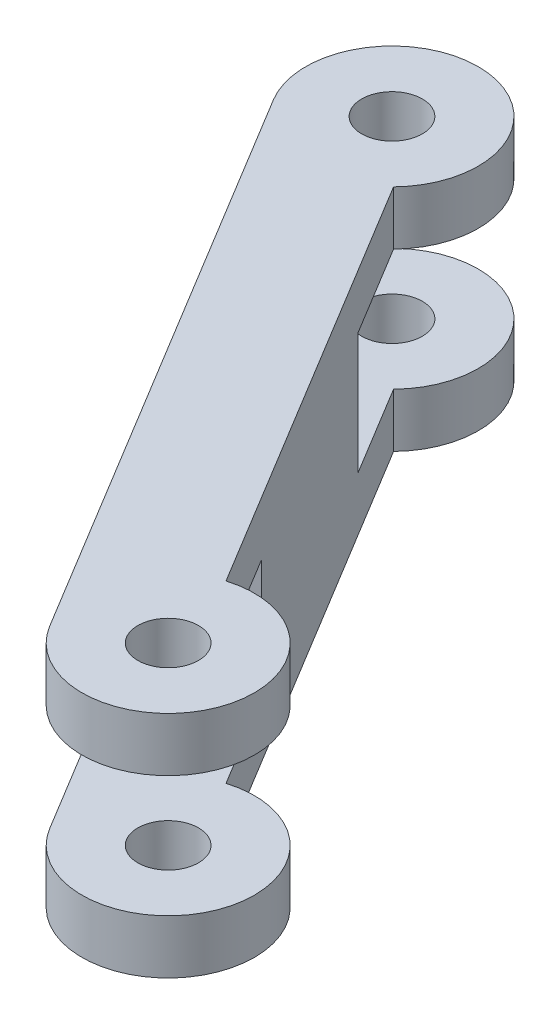
SolidWorks part; units mm, degrees
ref_plane "Front Plane" through (0, 0, 0) normal (0, 0, 1) x (1, 0, 0)
ref_plane "Top Plane" through (0, 0, 0) normal (0, 1, 0) x (1, 0, 0)
ref_plane "Right Plane" through (0, 0, 0) normal (1, 0, 0) x (0, 0, -1)
sketch "Sketch1" plane through (0, 0, 0) normal (0, 1, 0) x (1, 0, 0)
  line L0 (47.2297, 219.0186) -> (732.563, 219.0186) construction
  line L1 (-27.0937, 63.4834) -> (-14.3301, 42.4175)
  line L2 (-22.0655, 62.9079) -> (-12.5124, 47.1409)
  arc A0 (-22.0655, 62.9079) -> (-27.0937, 63.4834) centre (-24.3568, 65.1416) ccw
  circle A1 centre (-24.3568, 65.1416) radius 1.125
  arc A2 (-14.3301, 42.4175) -> (-12.5124, 47.1409) centre (-11.5933, 44.0757) ccw
  circle A3 centre (-11.5933, 44.0757) radius 1.125
extrude "Boss-Extrude5" add sketch "Sketch1" along normal blind 8.5
sketch "Sketch3" plane through (8.3169, 0, -5.0391) normal (-0.8553, 0, 0.5182) x (0.5182, 0, 0.8553)
  line L0 (-68.3348, 0) -> (-43.7039, 0) construction
  line L1 (-61.3348, 6.5) -> (-77.3331, 6.5)
  line L2 (-61.3348, 6.5) -> (-61.3348, 2)
  line L3 (-61.3348, 2) -> (-77.3331, 2)
  line L4 (-77.3331, 6.5) -> (-77.3331, 2)
  line L5 (-68.3348, 8.5) -> (-68.3348, 0) construction
  line L6 (-43.7039, 8.5) -> (-43.7039, 0) construction
  line L7 (-50.7039, 2) -> (-35.9219, 2)
  line L8 (-50.7039, 2) -> (-50.7039, 6.5)
  line L9 (-50.7039, 6.5) -> (-35.9219, 6.5)
  line L10 (-35.9219, 2) -> (-35.9219, 6.5)
  dimension "D1" = 4.5
  dimension "D2" = 2
  dimension "D3" = 7
  dimension "D4" = 7
extrude "Cut-Extrude1" cut sketch "Sketch3" against normal blind 8.5
